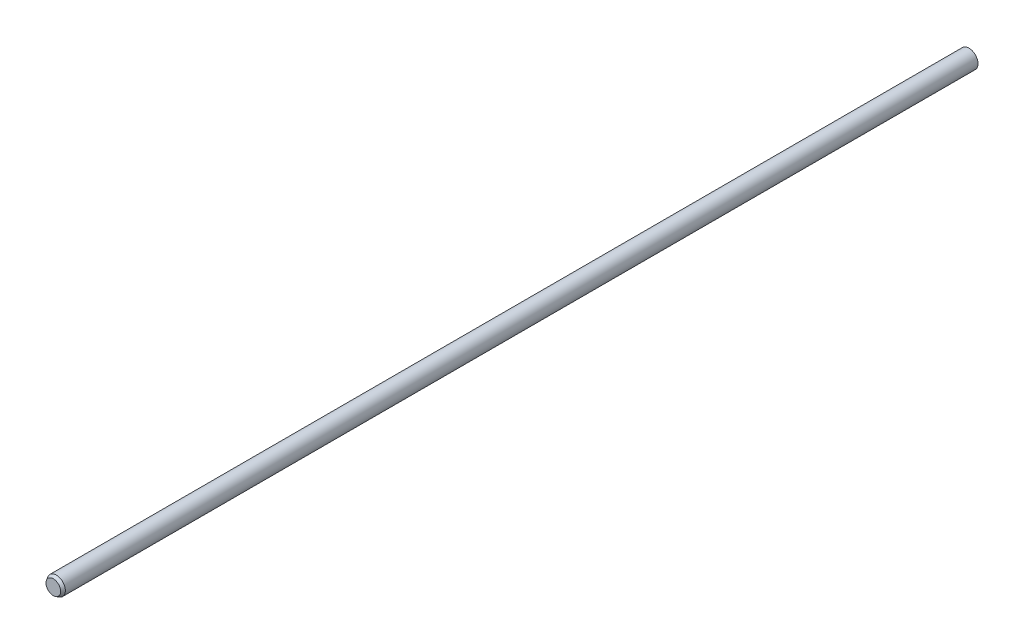
SolidWorks part; units mm, degrees
material "1060 Alloy"
ref_plane "Front Plane" through (0, 0, 0) normal (0, 0, 1) x (1, 0, 0)
ref_plane "Top Plane" through (0, 0, 0) normal (0, 1, 0) x (1, 0, 0)
ref_plane "Right Plane" through (0, 0, 0) normal (1, 0, 0) x (0, 0, -1)
sketch "Sketch1" plane through (0, 0, 0) normal (0, 0, 1) x (1, 0, 0)
  circle A0 centre (0, 0) radius 3
extrude "Boss-Extrude1" add sketch "Sketch1" along normal blind 304
chamfer "Chamfer1" distance 1 angle 30 2 edges at (3, 0, 304) (3, 0, 0)
